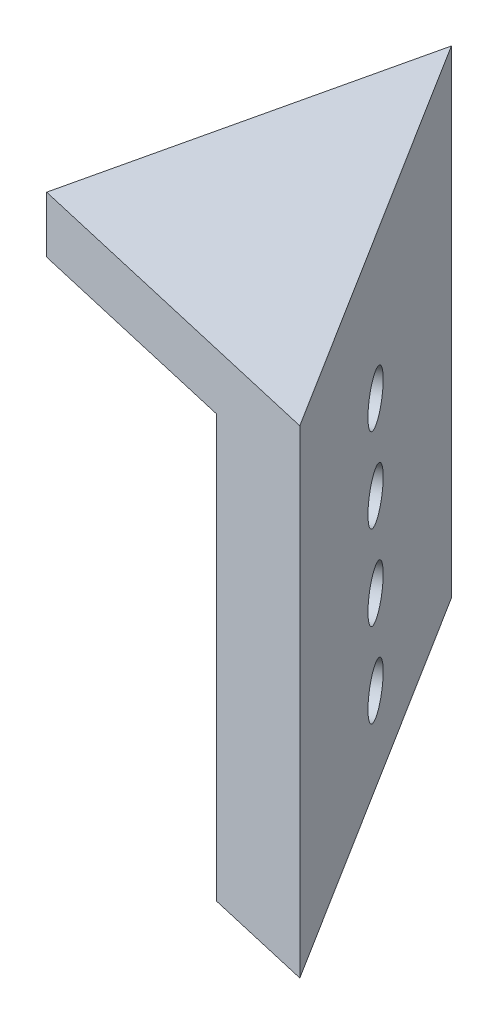
SolidWorks part; units mm, degrees
ref_plane "Front Plane" through (0, 0, 0) normal (0, 0, 1) x (1, 0, 0)
ref_plane "Top Plane" through (0, 0, 0) normal (0, 1, 0) x (1, 0, 0)
ref_plane "Right Plane" through (0, 0, 0) normal (1, 0, 0) x (0, 0, -1)
sketch "Sketch1" plane through (0, 0, 0) normal (0, 1, 0) x (1, 0, 0)
  line L0 (0, 0) -> (148.5106, -34.2106)
  line L1 (0, 0) -> (34.2106, 148.5106)
  line L2 (148.5106, -34.2106) -> (34.2106, 148.5106)
  dimension "D1" = 45
  dimension "D2" = 90
  dimension "D3" = 45
  dimension "D4" = 114.3
  dimension "D5" = 152.4
  dimension "D6" = 152.4
extrude "Boss-Extrude1" add sketch "Sketch1" along normal blind 25.4
sketch "Sketch2" plane through (0, 25.4, 0) normal (0, 1, 0) x (1, 0, 0)
  line L0 (34.2106, 148.5106) -> (22.9835, 99.7732)
  line L1 (34.2106, 148.5106) -> (0, 0) construction
  line L2 (34.2106, 148.5106) -> (148.5106, -34.2106)
  line L3 (148.5106, -34.2106) -> (34.2106, 148.5106) construction
  line L4 (0, 0) -> (148.5106, -34.2106) construction
  line L5 (148.5106, -34.2106) -> (99.7732, -22.9835)
  line L6 (99.7732, -22.9835) -> (22.9835, 99.7732)
extrude "Boss-Extrude2" add sketch "Sketch2" against normal blind 215.9
sketch "Sketch3" plane through (61.3784, 0, -38.3948) normal (-0.8478, 0, 0.5303) x (0.5303, 0, 0.8478)
  line L0 (-72.398, -38.1) -> (0, -38.1) construction
  line L1 (-72.398, -190.5) -> (-72.398, 0) construction
  line L2 (0, -38.1) -> (72.398, -38.1) construction
  line L3 (72.398, -190.5) -> (72.398, 0) construction
  line L4 (-72.398, -76.2) -> (0, -76.2) construction
  line L5 (0, -76.2) -> (72.398, -76.2) construction
  line L6 (-72.398, -114.3) -> (0, -114.3) construction
  line L7 (0, -114.3) -> (72.398, -114.3) construction
  line L8 (-72.398, -152.4) -> (0, -152.4) construction
  line L9 (0, -152.4) -> (72.398, -152.4) construction
  line L10 (0, 0) -> (0, -38.1) construction
  line L11 (0, -38.1) -> (0, -76.2) construction
  line L12 (0, -76.2) -> (0, -114.3) construction
  line L13 (0, -114.3) -> (0, -152.4) construction
  line L14 (0, -152.4) -> (0, -190.5) construction
  line L15 (-72.398, -190.5) -> (72.398, -190.5) construction
  circle A3 centre (0, -38.1) radius 10.795
  circle A5 centre (0, -114.3) radius 10.795
  circle A6 centre (0, -152.4) radius 10.795
  circle A7 centre (0, -76.2) radius 10.795
  dimension "D2" = 21.59
extrude "Cut-Extrude1" cut sketch "Sketch3" against normal blind 381
